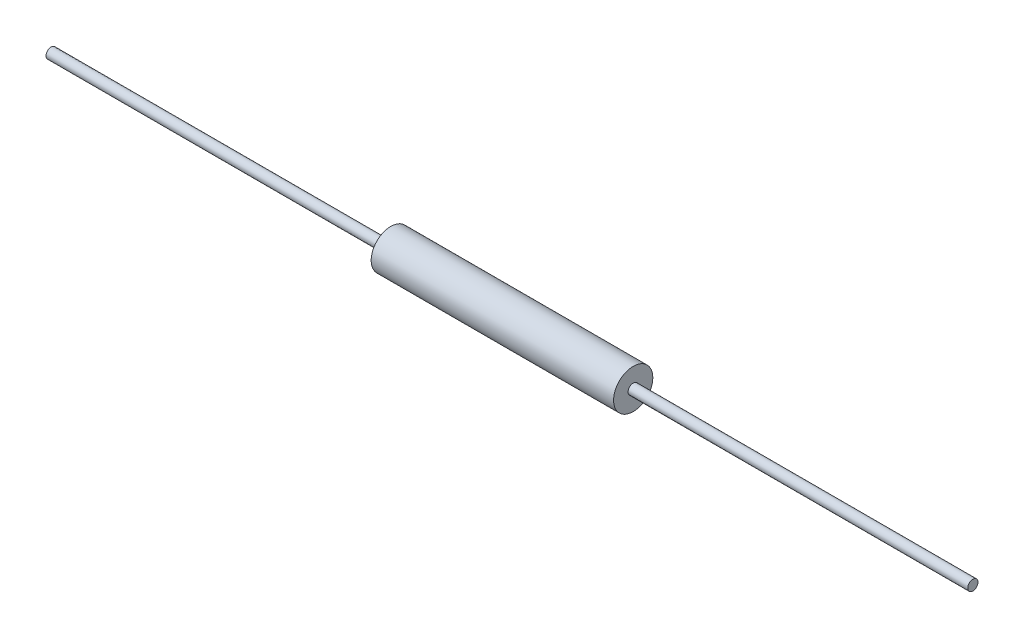
SolidWorks part; units mm, degrees
ref_plane "Front Plane" through (0, 0, 0) normal (0, 0, 1) x (1, 0, 0)
ref_plane "Top Plane" through (0, 0, 0) normal (0, 1, 0) x (1, 0, 0)
ref_plane "Right Plane" through (0, 0, 0) normal (1, 0, 0) x (0, 0, -1)
sketch "Sketch1" plane through (0, 0, 0) normal (1, 0, 0) x (0, 0, -1)
  circle A0 centre (0, 0) radius 1.15
  dimension "D1" = 2.3
extrude "Boss-Extrude1" add sketch "Sketch1" along normal blind 14.2
sketch "Sketch2" plane through (14.2, 0, 0) normal (1, 0, 0) x (0, 0, -1)
  circle A0 centre (0, 0) radius 0.3
  dimension "D1" = 0.6
extrude "Boss-Extrude2" add sketch "Sketch2" along normal blind 19.9
sketch "Sketch3" plane through (0, 0, 0) normal (-1, 0, 0) x (0, 0, 1)
  circle A0 centre (0, 0) radius 0.3
  dimension "D1" = 0.6
extrude "Boss-Extrude3" add sketch "Sketch3" along normal blind 19.9
